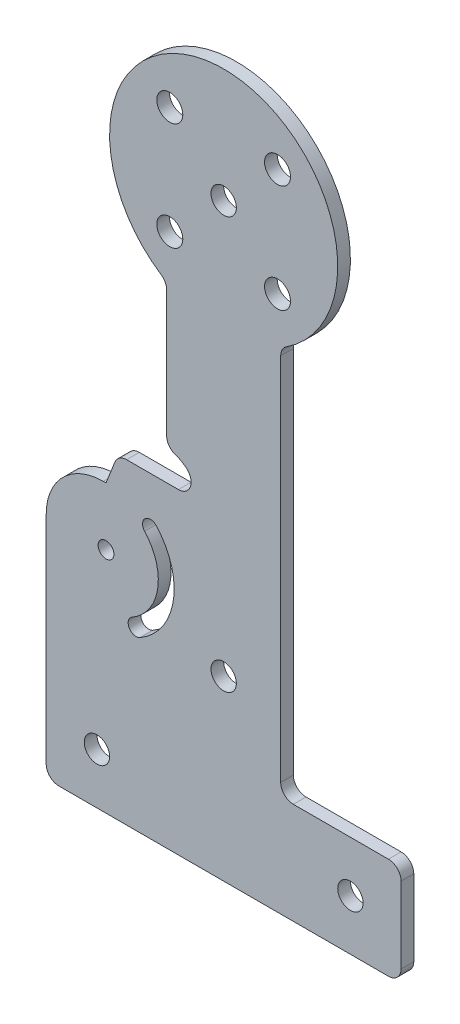
SolidWorks part; units mm, degrees
ref_plane "前视基准面" through (0, 0, 0) normal (0, 0, 1) x (1, 0, 0)
ref_plane "上视基准面" through (0, 0, 0) normal (0, 1, 0) x (1, 0, 0)
ref_plane "右视基准面" through (0, 0, 0) normal (1, 0, 0) x (0, 0, -1)
sketch "草图1" plane through (0, 0, 0) normal (0, 0, 1) x (1, 0, 0)
  line L2 (-13.3404, 23.3177) -> (-13.3404, 108.3177) construction
  line L3 (-13.3404, 108.3177) -> (-7.3404, 108.3177) construction
  line L6 (14.6596, 15.3177) -> (14.6596, 31.3177)
  line L9 (-41.3404, 15.3177) -> (-41.3404, 31.3177)
  line L11 (-41.3404, 31.3177) -> (-22.3404, 31.3177) construction
  line L14 (-33.3404, 23.3177) -> (-13.3404, 23.3177) construction
  line L15 (-13.3404, 23.3177) -> (6.6596, 23.3177) construction
  line L16 (-4.3404, 31.3177) -> (14.6596, 31.3177)
  line L17 (-41.3404, 15.3177) -> (14.6596, 15.3177)
  line L18 (-13.3404, 108.3177) -> (-13.3404, 116.8177) construction
  line L19 (-13.3404, 116.8177) -> (-4.8404, 116.8177) construction
  line L20 (-4.3404, 31.3177) -> (-4.3404, 92.7292)
  line L21 (-22.3404, 31.3177) -> (-22.3404, 92.7292) construction
  line L22 (-22.3404, 92.7292) -> (-22.3404, 69.9893)
  line L23 (-22.3404, 60.5237) -> (-22.3404, 31.3177) construction
  line L30 (-41.3404, 60.4565) -> (-41.3404, 31.3177)
  line L31 (-41.3404, 60.4565) -> (-31.9023, 60.4565)
  line L32 (-31.9023, 60.4565) -> (-30.0099, 65.2565)
  line L33 (-30.0099, 65.2565) -> (-17.6076, 65.2565)
  circle A4 centre (-33.3404, 23.3177) radius 2
  circle A5 centre (6.6596, 23.3177) radius 2
  circle A9 centre (-13.3404, 108.3177) radius 2
  circle A12 centre (-13.3404, 43.3177) radius 2
  circle A13 centre (-4.8404, 116.8177) radius 2.05
  circle A17 centre (-13.3404, 108.3177) radius 18 construction
  arc A18 (-22.3404, 92.7292) -> (-4.3404, 92.7292) centre (-13.3404, 108.3177) cw
  arc A20 (-22.3404, 69.9893) -> (-22.3404, 60.5237) centre (-22.3404, 65.2565) cw construction
  circle A23 centre (-31.9023, 51.3177) radius 1.25
  circle A31 centre (-31.9023, 51.3177) radius 9.5 construction
  arc A32 (-24.8954, 57.7327) -> (-27.1601, 43.0859) centre (-31.9023, 51.3177) cw construction
  arc A33 (-26.5362, 42.0028) -> (-23.9734, 58.5768) centre (-31.9023, 51.3177) ccw
  arc A34 (-27.7841, 44.1691) -> (-25.8173, 56.8886) centre (-31.9023, 51.3177) ccw
  arc A35 (-27.7841, 44.1691) -> (-26.5362, 42.0028) centre (-27.1601, 43.0859) ccw
  arc A36 (-23.9734, 58.5768) -> (-25.8173, 56.8886) centre (-24.8954, 57.7327) ccw
  circle A37 centre (-4.8404, 99.8177) radius 2.05
  circle A38 centre (-21.8404, 99.8177) radius 2.05
  circle A39 centre (-21.8404, 116.8177) radius 2.05
  arc A40 (-22.3404, 69.9893) -> (-17.6076, 65.2565) centre (-22.3404, 65.2565) cw
  point P31 (-22.5139, 49.866)
  dimension "D5" = 4
  dimension "D6" = 2.5
  dimension "D7" = 4
  dimension "D8" = 65
  dimension "D13" = 19
  dimension "D14" = 28
  dimension "D2" = 20
  dimension "D3" = 8
  dimension "D4" = 8
  dimension "D9" = 8
  dimension "D10" = 20
  dimension "D11" = 20
  dimension "D12" = 8
  dimension "D15" = 4.8
  dimension "D16" = 45.1388
extrude "凸台-拉伸1" add sketch "草图1" along normal blind 2
fillet "圆角1" radius 2 9 edges at (14.6596, 31.3177, 1) (14.6596, 15.3177, 1) (-41.3404, 15.3177, 1) (-4.3404, 31.3177, 1) (-17.6076, 65.2565, 1) (-22.3404, 69.9893, 1) (-30.0099, 65.2565, 1) (-4.3404, 92.7292, 1) (-22.3404, 92.7292, 1)
fillet "圆角3" radius 9 1 edges at (-41.3404, 60.4565, 1)
